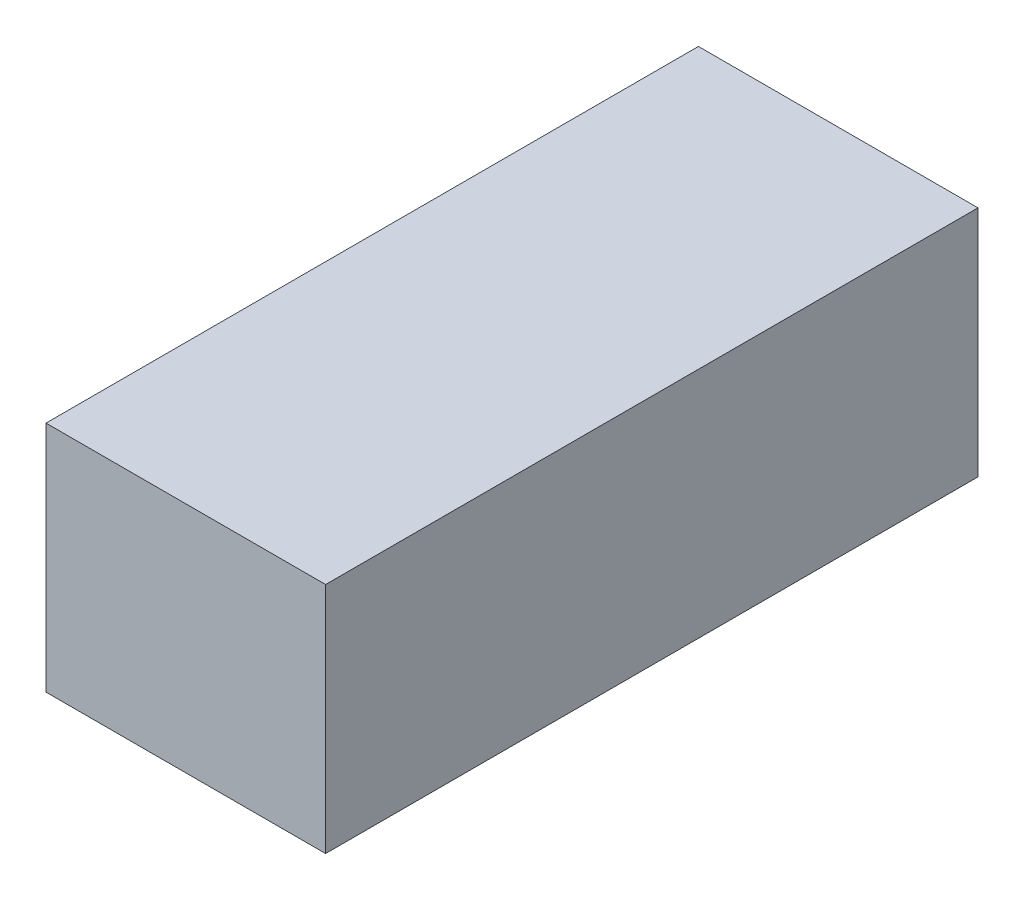
SolidWorks part; units mm, degrees
ref_plane "前视基准面" through (0, 0, 0) normal (0, 0, 1) x (1, 0, 0)
ref_plane "上视基准面" through (0, 0, 0) normal (0, 1, 0) x (1, 0, 0)
ref_plane "右视基准面" through (0, 0, 0) normal (1, 0, 0) x (0, 0, -1)
sketch "草图1" plane through (0, 0, 0) normal (0, 0, 1) x (1, 0, 0)
  line L1 (0, 0) -> (18, 0)
  line L2 (0, 0) -> (0, -15)
  line L3 (0, -15) -> (18, -15)
  line L4 (18, 0) -> (18, -15)
  dimension "D1" = 18
  dimension "D2" = 15
extrude "凸台-拉伸1" add sketch "草图1" along normal blind 42
